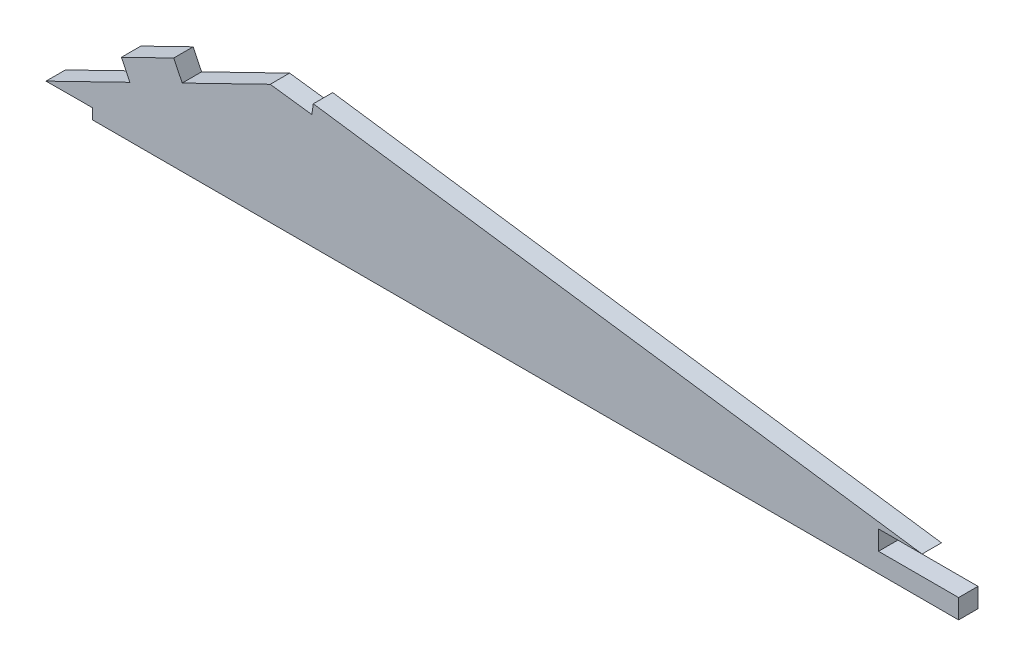
SolidWorks part; units mm, degrees
ref_plane "前视基准面" through (0, 0, 0) normal (0, 0, 1) x (1, 0, 0)
ref_plane "上视基准面" through (0, 0, 0) normal (0, 1, 0) x (1, 0, 0)
ref_plane "右视基准面" through (0, 0, 0) normal (1, 0, 0) x (0, 0, -1)
sketch "Model" plane through (0, 0, 0) normal (0, 0, 1) x (1, 0, 0)
  line L0 (10.8739, 9.301) -> (9.9972, 11.0986)
  line L1 (9.9972, 11.0986) -> (15.39, 13.7288)
  line L2 (15.39, 13.7288) -> (16.2667, 11.9312)
  line L3 (10.8739, 9.301) -> (2.2239, 5.0821)
  line L4 (16.2667, 11.9312) -> (25.3361, 16.3546)
  line L5 (7.0096, 4.0175) -> (96.2983, 4.0175)
  line L6 (7.0096, 4.0175) -> (7.0054, 5.1006)
  line L7 (7.0054, 5.1006) -> (2.2239, 5.0821)
  line L8 (88.0421, 6.0175) -> (96.2983, 6.0175)
  line L9 (88.0421, 8.0175) -> (92.5318, 8.0175)
  line L10 (88.0421, 6.0175) -> (88.0421, 8.0175)
  line L11 (96.2983, 4.0175) -> (96.2983, 6.0175)
  line L12 (29.7785, 16.8369) -> (92.5318, 8.0175)
  line L13 (25.3361, 16.3546) -> (29.6303, 15.7992)
  line L14 (29.6303, 15.7992) -> (29.7785, 16.8369)
extrude "凸台-拉伸1" add sketch "Model" along normal blind 2
